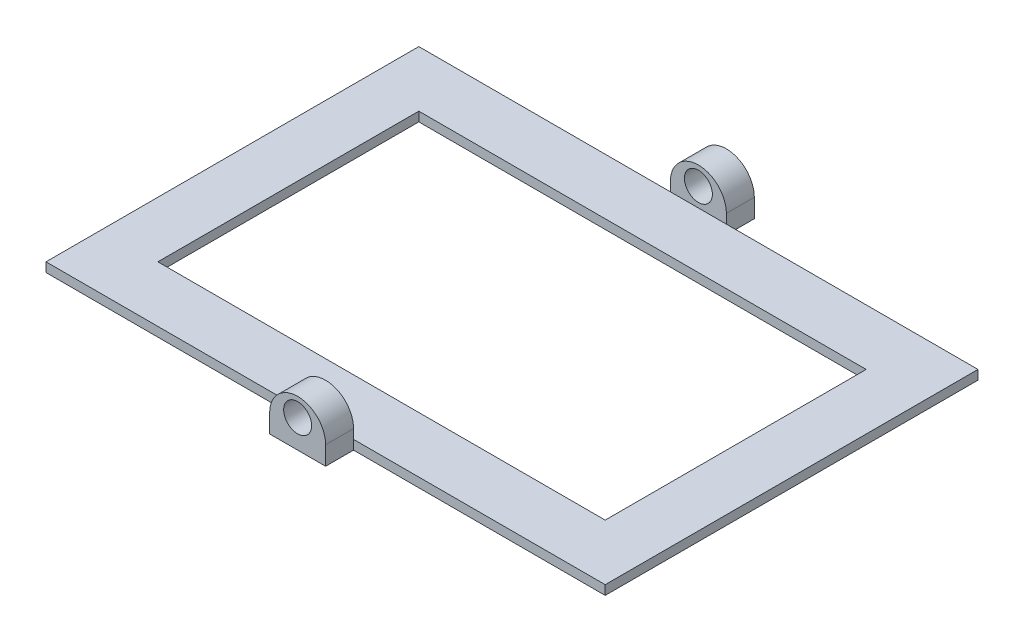
SolidWorks part; units mm, degrees
ref_plane "Front Plane" through (0, 0, 0) normal (0, 0, 1) x (1, 0, 0)
ref_plane "Top Plane" through (0, 0, 0) normal (0, 1, 0) x (1, 0, 0)
ref_plane "Right Plane" through (0, 0, 0) normal (1, 0, 0) x (0, 0, -1)
sketch "Sketch1" plane through (0, 0, 0) normal (0, 1, 0) x (1, 0, 0)
  line L0 (34.8836, 1.9321) -> (-205.1164, 1.9321)
  line L1 (64.8836, -168.0679) -> (-235.1164, -168.0679)
  line L2 (64.8836, -168.0679) -> (64.8836, 31.9321)
  line L3 (64.8836, 31.9321) -> (-235.1164, 31.9321)
  line L4 (-235.1164, -168.0679) -> (-235.1164, 31.9321)
  line L5 (64.8836, -168.0679) -> (-235.1164, 31.9321) construction
  line L6 (64.8836, 31.9321) -> (-235.1164, -168.0679) construction
  line L7 (-205.1164, -138.0679) -> (-205.1164, 1.9321)
  line L8 (34.8836, -138.0679) -> (-205.1164, -138.0679)
  line L9 (34.8836, -138.0679) -> (34.8836, 1.9321)
  point P0 (-85.1164, -68.0679)
  dimension "D1" = 300
  dimension "D2" = 200
  dimension "D3" = 30
extrude "Boss-Extrude1" add sketch "Sketch1" along normal blind 5
sketch "Sketch2" plane through (0, 0, 168.0679) normal (0, 0, 1) x (1, 0, 0)
  line L0 (-235.1164, 5) -> (64.8836, 5)
  line L1 (-205.1164, 5) -> (34.8836, 5) construction
sketch "Sketch3" plane through (0, 0, 168.0679) normal (0, 0, 1) x (1, 0, 0)
  line L0 (-235.1164, 0) -> (64.8836, 0) construction
  line L5 (-235.1164, 5) -> (64.8836, 5) construction
  line L6 (64.8836, 5) -> (64.8836, 0) construction
  line L7 (-100.1164, 0) -> (-70.1164, 0)
  line L8 (-100.1164, 0) -> (-100.1164, 10)
  line L10 (-70.1164, 0) -> (-70.1164, 10)
  line L11 (-100.1164, 0) -> (-70.1164, 10) construction
  line L12 (-100.1164, 10) -> (-70.1164, 0) construction
  arc A0 (-100.1164, 10) -> (-70.1164, 10) centre (-85.1164, 10) cw
  circle A1 centre (-85.1164, 15.0717) radius 7.5
  point P0 (-85.6764, 0)
  point P3 (-85.1164, 5)
  dimension "D3" = 15
  dimension "D1" = 10
  dimension "D2" = 30
extrude "Boss-Extrude2" add sketch "Sketch3" along normal blind 15
ref_plane "Plane1" through (0, 0, 68.0679) normal (0, 0, 1) x (1, 0, 0)
mirror "Mirror1" about plane through (0, 0, 68.0679) normal (0, 0, 1) of "Boss-Extrude2"
sketch "Sketch4" plane through (0, 0, 0) normal (0, -1, 0) x (1, 0, 0)
  line L0 (-235.1164, 68.0679) -> (64.8836, 68.0679) construction
  line L1 (-235.1164, -31.9321) -> (-235.1164, 168.0679) construction
  line L2 (64.8836, 168.0679) -> (64.8836, -31.9321) construction
  circle A0 centre (51.9604, 68.0679) radius 9.5529
  circle A1 centre (51.9604, 68.0679) radius 7.42
